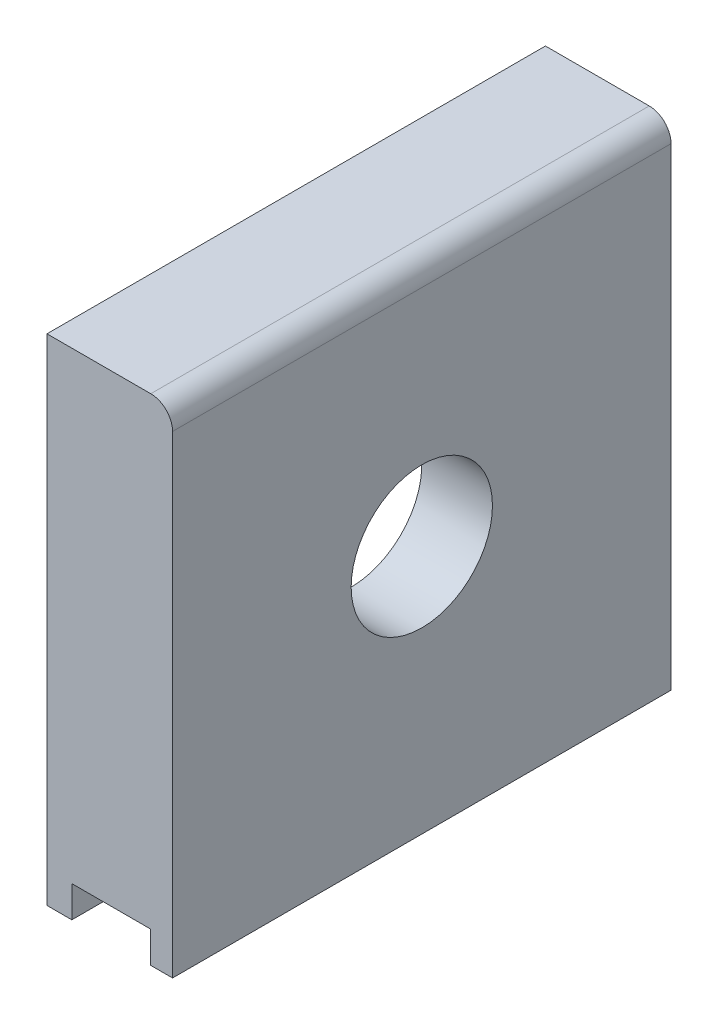
SolidWorks part; units mm, degrees
ref_plane "Front Plane" through (0, 0, 0) normal (0, 0, 1) x (1, 0, 0)
ref_plane "Top Plane" through (0, 0, 0) normal (0, 1, 0) x (1, 0, 0)
ref_plane "Right Plane" through (0, 0, 0) normal (1, 0, 0) x (0, 0, -1)
sketch "Sketch1" plane through (0, 0, 0) normal (0, 0, 1) x (1, 0, 0)
  line L2 (-22.225, -58.3537) -> (-22.225, -28.2045) construction
  line L5 (-59.0915, -26.617) -> (-23.8125, -26.617) construction
  line L6 (-22.225, -58.3537) -> (-22.225, -28.2045)
  line L7 (-59.0915, -26.617) -> (-23.8125, -26.617)
  line L9 (-22.425, -58.3537) -> (-22.425, -28.2045)
  line L10 (-22.425, -58.3537) -> (-30.425, -58.3537)
  line L12 (46.9282, -58.3537) -> (-22.225, -58.3537) construction
  line L13 (46.9282, -58.3537) -> (-22.225, -58.3537)
  line L14 (-59.0915, -26.817) -> (-23.8125, -26.817) construction
  line L15 (-23.8125, -26.817) -> (-30.425, -26.817)
  line L16 (-30.425, -26.817) -> (-30.425, -58.3537)
  arc A2 (-22.225, -28.2045) -> (-23.8125, -26.617) centre (-23.8125, -28.2045) ccw construction
  arc A3 (-22.225, -28.2045) -> (-23.8125, -26.617) centre (-23.8125, -28.2045) ccw
  arc A4 (-22.425, -28.2045) -> (-23.8125, -26.817) centre (-23.8125, -28.2045) ccw
  dimension "D2" = 8
  dimension "D1" = 0.2
extrude "Boss-Extrude1" add sketch "Sketch1" against normal up to surface (31.75 mm away) contours L9 A4 L15 L16 L10
sketch "Sketch2" plane through (-30.425, 0, 0) normal (-1, 0, 0) x (0, 0, 1)
  circle A0 centre (-15.875, -42.4787) radius 11.25
  circle A1 centre (-15.875, -42.4787) radius 4.5
  dimension "D1" = 22.5
  dimension "D2" = 9
extrude "Cut-Extrude1" cut sketch "Sketch2" against normal blind 3.5
sketch "Sketch3" plane through (-30.425, 0, 0) normal (-1, 0, 0) x (0, 0, 1)
  circle A0 centre (-15.875, -42.4787) radius 4.5 construction
  circle A1 centre (-15.875, -42.4787) radius 4.5
extrude "Cut-Extrude2" cut sketch "Sketch3" against normal up to next
sketch "Sketch4" plane through (0, -58.3537, 0) normal (0, -1, 0) x (1, 0, 0)
  line L0 (-22.425, 0) -> (-30.425, 0) construction
  line L1 (-23.8412, -31.75) -> (-28.8412, -31.75)
  line L2 (-23.8412, -31.75) -> (-23.8412, 0)
  line L3 (-23.8412, 0) -> (-28.8412, 0)
  line L4 (-28.8412, -31.75) -> (-28.8412, 0)
  line L5 (-23.8412, -31.75) -> (-28.8412, 0) construction
  line L6 (-23.8412, 0) -> (-28.8412, -31.75) construction
  line L10 (-30.425, -31.75) -> (-22.425, -31.75) construction
  line L11 (-22.425, -31.75) -> (-26.3412, -31.75) construction
  line L12 (-26.3412, -31.75) -> (-26.3412, -15.875) construction
  point P0 (-26.3412, -15.875)
  dimension "D1" = 5
extrude "Cut-Extrude3" cut sketch "Sketch4" against normal blind 2
chamfer "Chamfer3" distance 0.25 angle 45 1 edges at (-30.425, -42.4787, -4.625)
